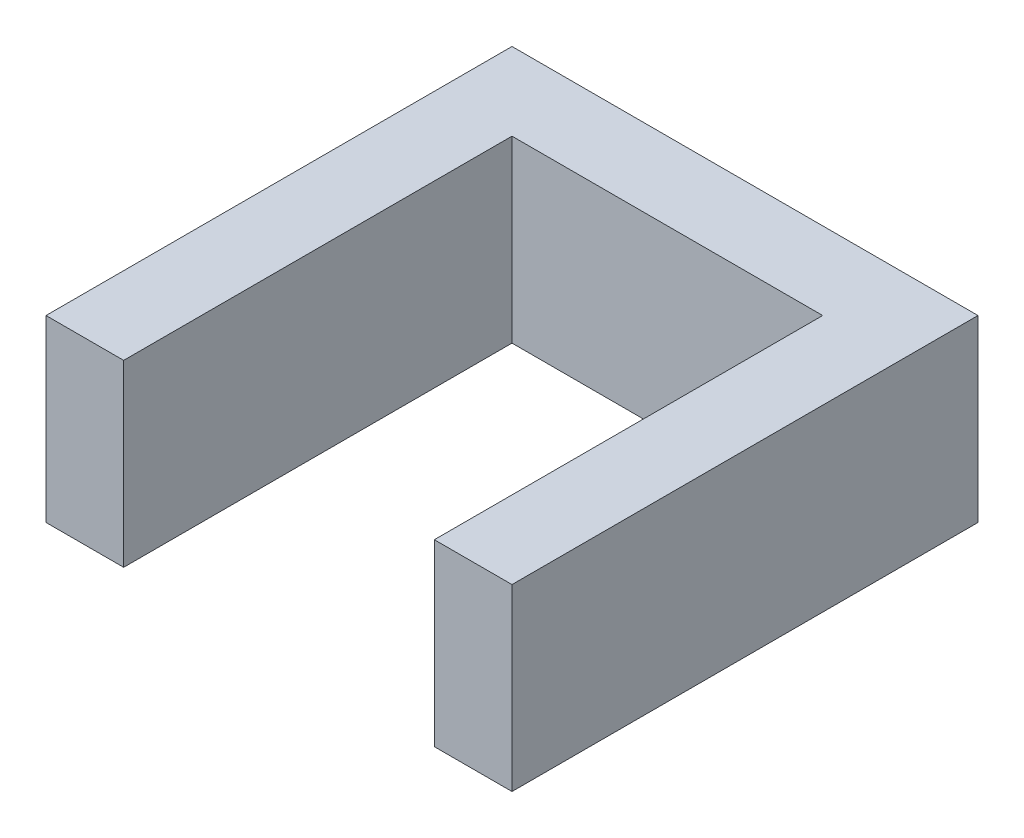
SolidWorks part; units mm, degrees
material "ABS"
ref_plane "Front" through (0, 0, 0) normal (0, 0, 1) x (1, 0, 0)
ref_plane "Top" through (0, 0, 0) normal (0, 1, 0) x (1, 0, 0)
ref_plane "Right" through (0, 0, 0) normal (1, 0, 0) x (0, 0, -1)
sketch "Sketch1" plane through (0, 0, 0) normal (0, 1, 0) x (1, 0, 0)
  line L0 (0, 0) -> (0, 30)
  line L1 (0, 30) -> (30, 30)
  line L2 (30, 30) -> (30, 0)
  line L3 (30, 0) -> (25, 0)
  line L4 (5, 0) -> (5, 25)
  line L5 (5, 25) -> (25, 25)
  line L6 (25, 25) -> (25, 0)
  line L7 (5, 0) -> (0, 0)
  dimension "D1" = 20
  dimension "D2" = 25
  dimension "D3" = 30
  dimension "D4" = 30
  dimension "D5" = 5
extrude "Boss-Extrude1" add sketch "Sketch1" along normal blind 11.54
